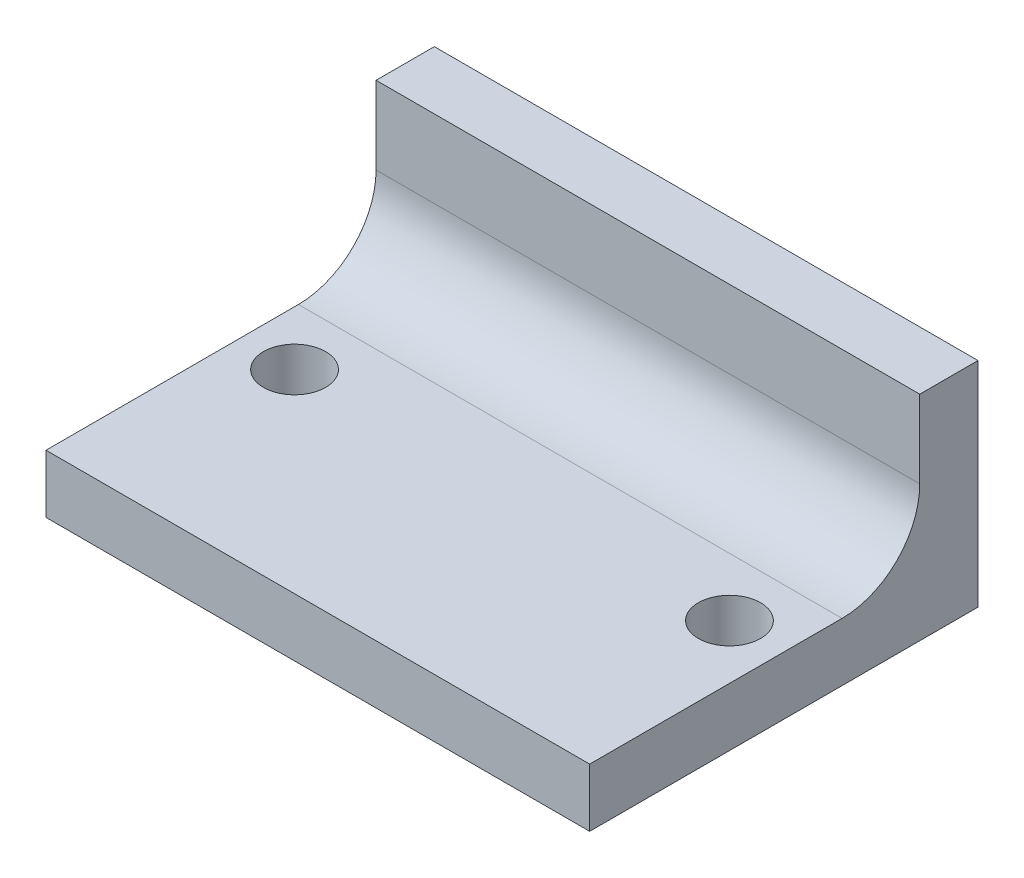
SolidWorks part; units mm, degrees
ref_plane "Front Plane" through (0, 0, 0) normal (0, 0, 1) x (1, 0, 0)
ref_plane "Top Plane" through (0, 0, 0) normal (0, 1, 0) x (1, 0, 0)
ref_plane "Right Plane" through (0, 0, 0) normal (1, 0, 0) x (0, 0, -1)
sketch "Sketch3" plane through (0, 0, 0) normal (0, 1, 0) x (1, 0, 0)
  line L0 (4.4691, 25.0711) -> (4.4691, -24.9289) construction
  line L1 (-30.5309, 25.0711) -> (39.4691, 25.0711)
  line L2 (-30.5309, 25.0711) -> (-30.5309, -24.9289)
  line L3 (-30.5309, -24.9289) -> (39.4691, -24.9289)
  line L4 (39.4691, 25.0711) -> (39.4691, -24.9289)
  line L5 (-30.5309, 0.0711) -> (39.4691, 0.0711) construction
  line L6 (4.4691, 0.0711) -> (29.4691, 0.0711) construction
  line L7 (4.4691, 0.0711) -> (36.4691, 0.0711) construction
  line L8 (4.4691, 0.0711) -> (28.4691, 0.0711) construction
  line L9 (28.4691, 0.0711) -> (36.4691, 0.0711) construction
  circle A0 centre (32.4691, 0.0711) radius 4
  circle A1 centre (-23.5309, 0.0711) radius 4
extrude "Boss-Extrude1" add sketch "Sketch3" along normal blind 7.5
sketch "Sketch4" plane through (0, 7.5, 0) normal (0, 1, 0) x (1, 0, 0)
  line L0 (39.4691, -24.9289) -> (39.4691, 25.0711) construction
  line L1 (-30.5309, 25.0711) -> (39.4691, 25.0711)
  line L2 (-30.5309, 25.0711) -> (-30.5309, 17.5711)
  line L3 (-30.5309, 17.5711) -> (39.4691, 17.5711)
  line L4 (39.4691, 25.0711) -> (39.4691, 17.5711)
extrude "Boss-Extrude2" add sketch "Sketch4" along normal blind 20
fillet "Fillet3" radius 10 1 edges at (4.4691, 7.5, -17.5711)
